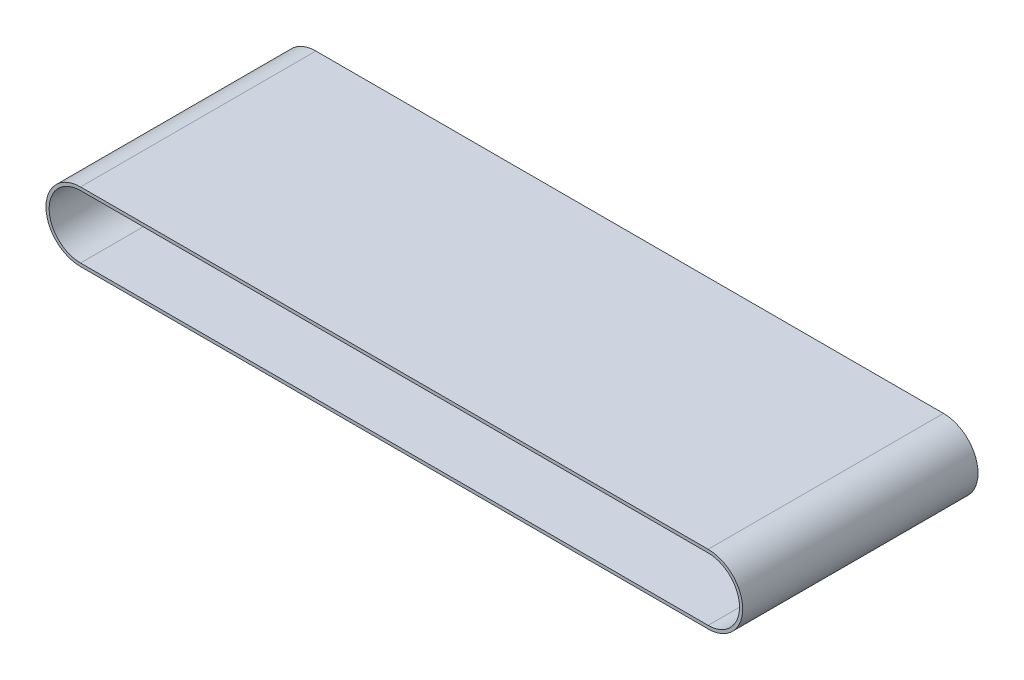
SolidWorks part; units mm, degrees
material "Silicon Rubber"
ref_plane "Front Plane" through (0, 0, 0) normal (0, 0, 1) x (1, 0, 0)
ref_plane "Top Plane" through (0, 0, 0) normal (0, 1, 0) x (1, 0, 0)
ref_plane "Right Plane" through (0, 0, 0) normal (1, 0, 0) x (0, 0, -1)
sketch "Sketch1" plane through (0, 0, 0) normal (0, 0, 1) x (1, 0, 0)
  line L0 (0, 0) -> (400, 0) construction
  line L1 (0, 20) -> (400, 20)
  line L2 (0, -20) -> (400, -20)
  line L3 (0, 22) -> (400, 22)
  line L4 (0, -22) -> (400, -22)
  arc A0 (0, 20) -> (0, -20) centre (0, 0) ccw
  arc A1 (400, -20) -> (400, 20) centre (400, 0) ccw
  arc A2 (400, -22) -> (400, 22) centre (400, 0) ccw
  arc A3 (0, 22) -> (0, -22) centre (0, 0) ccw
  point P3 (200, 0)
  dimension "D2" = 20
  dimension "D1" = 400
  dimension "D3" = 2
extrude "Boss-Extrude1" add sketch "Sketch1" along normal blind 150
